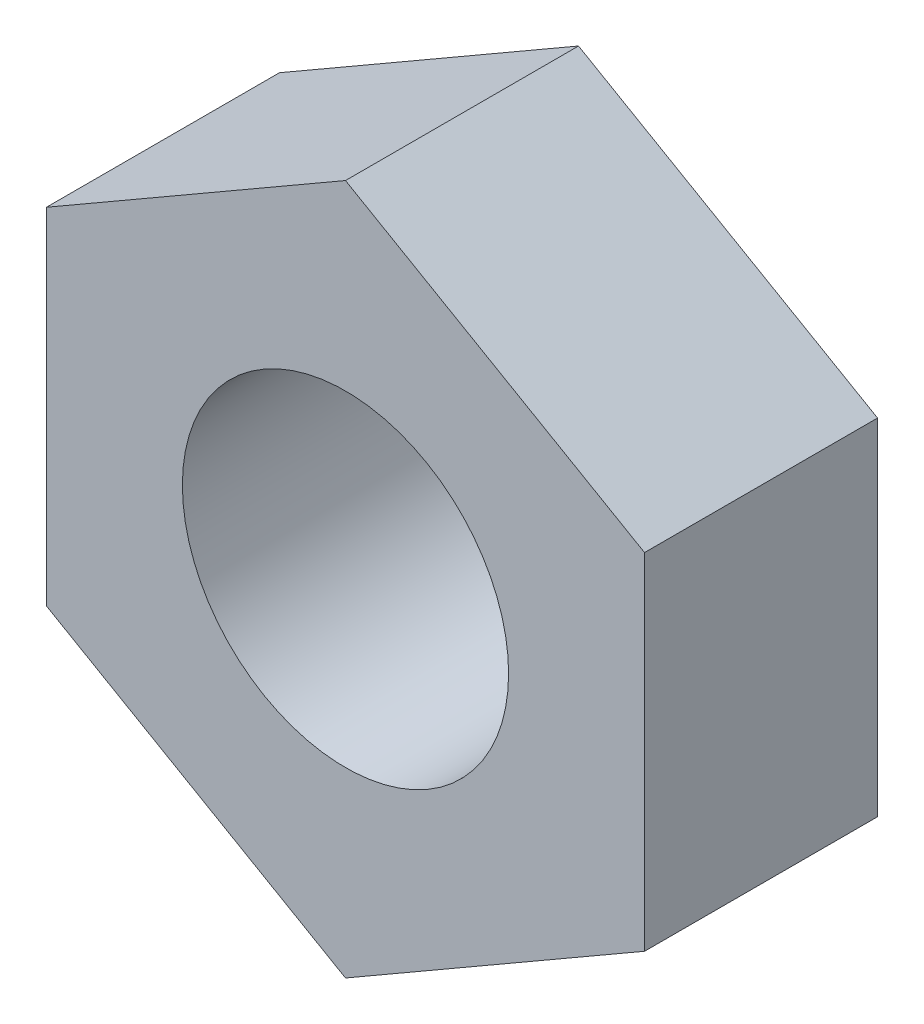
SolidWorks part; units mm, degrees
material "6061-T6 (SS)"
ref_plane "Front Plane" through (0, 0, 0) normal (1, 0, 0) x (0, 1, 0)
ref_plane "Top Plane" through (0, 0, 0) normal (0, 0, 1) x (0, 1, 0)
ref_plane "Right Plane" through (0, 0, 0) normal (0, 1, 0) x (-1, 0, 0)
sketch "Sketch1" plane through (0, 0, 0) normal (0, 0, 1) x (0, 1, 0)
  line L1 (-4.4456, 0) -> (-2.2228, -3.85)
  line L2 (-2.2228, -3.85) -> (2.2228, -3.85)
  line L3 (2.2228, -3.85) -> (4.4456, 0)
  line L4 (4.4456, 0) -> (2.2228, 3.85)
  line L5 (2.2228, 3.85) -> (-2.2228, 3.85)
  line L6 (-2.2228, 3.85) -> (-4.4456, 0)
  circle A0 centre (0, 0) radius 3.85 construction
  dimension "D1" = 7.7
extrude "Boss-Extrude1" add sketch "Sketch1" along normal blind 3
hole_wizard "Tap Drill for M5x0.8 Tap1" positions "Sketch2" profile "Sketch3" hole size "M5x0.8" standard "ANSI Metric" end condition through all
sketch "Sketch2" plane through (0, 0, 3) normal (0, 0, 1) x (1, 0, 0)
  point P0 (0, 0)
sketch "Sketch3" plane through (0, 0, 3) normal (1, 0, 0) x (0, -1, 0)
  line L0 (0, 0) -> (0, 3)
  line L1 (0, 3) -> (2.1, 3)
  line L2 (2.1, 3) -> (2.1, 0)
  line L5 (2.1, 0) -> (0, 0)
  line L11 (0, -6.35) -> (0, 107.95) construction
  dimension "Thru Hole Dia." = 4.2
  dimension "Thru Hole Depth" = 3
